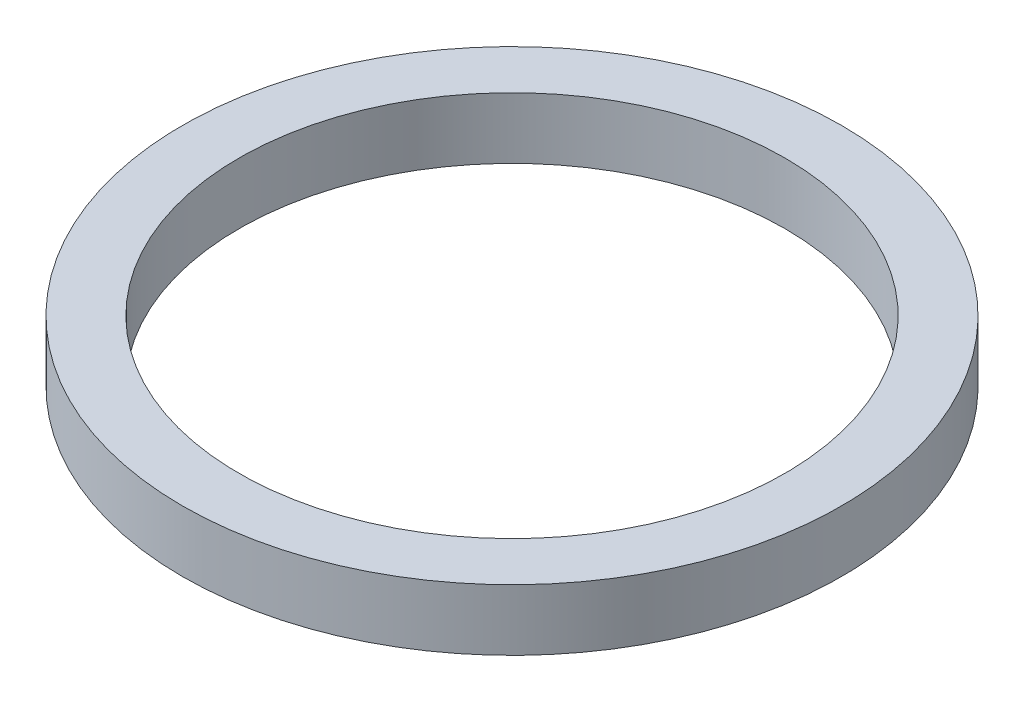
SolidWorks part; units mm, degrees
ref_plane "Alzado" through (0, 0, 0) normal (0, 0, 1) x (1, 0, 0)
ref_plane "Planta" through (0, 0, 0) normal (0, 1, 0) x (1, 0, 0)
ref_plane "Vista lateral" through (0, 0, 0) normal (1, 0, 0) x (0, 0, -1)
sketch "Croquis1" plane through (0, 0, 0) normal (0, 1, 0) x (1, 0, 0)
  circle A0 centre (0, 0) radius 35
  circle A1 centre (0, 0) radius 29
  dimension "D1" = 58
  dimension "D2" = 70
extrude "Saliente-Extruir1" add sketch "Croquis1" along normal blind 6.5
